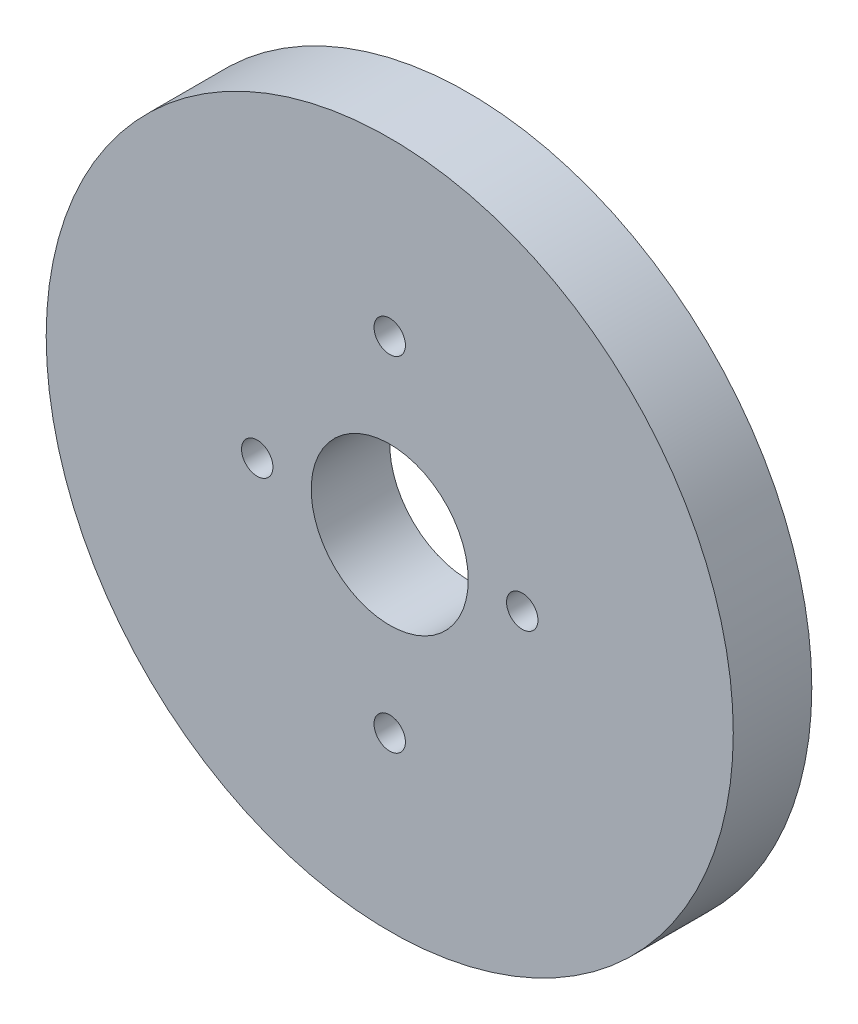
SolidWorks part; units mm, degrees
ref_plane "Front Plane" through (0, 0, 0) normal (0, 0, 1) x (1, 0, 0)
ref_plane "Top Plane" through (0, 0, 0) normal (0, 1, 0) x (1, 0, 0)
ref_plane "Right Plane" through (0, 0, 0) normal (1, 0, 0) x (0, 0, -1)
sketch "Sketch1" plane through (0, 0, 0) normal (0, 0, 1) x (1, 0, 0)
  line L0 (6.75, 0) -> (0, 0) construction
  line L1 (0, 0) -> (0, 8.75) construction
  circle A0 centre (0, 0) radius 17.5
  circle A1 centre (0, 0) radius 4
  circle A2 centre (6.75, 0) radius 0.8
  circle A3 centre (0, 8.75) radius 0.8
  circle A4 centre (0, -8.75) radius 0.8
  circle A5 centre (-6.75, 0) radius 0.8
  dimension "D1" = 8
  dimension "D2" = 35
  dimension "D5" = 1.6
  dimension "D3" = 6.75
  dimension "D4" = 8.75
extrude "Boss-Extrude1" add sketch "Sketch1" along normal blind 4
